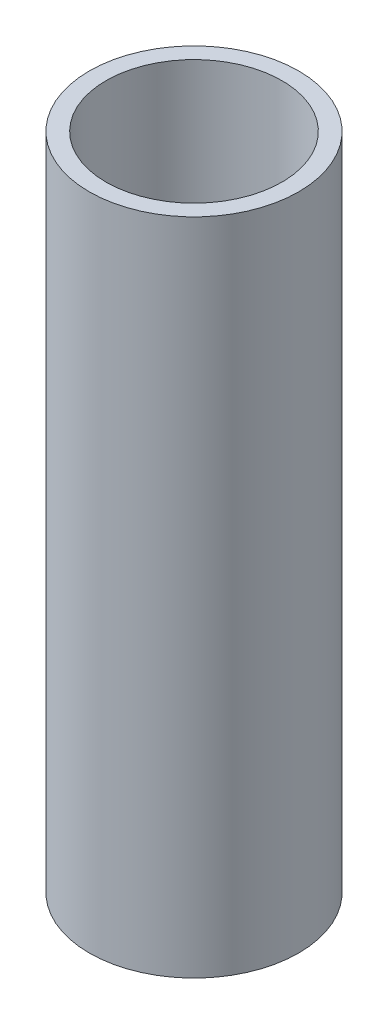
SolidWorks part; units mm, degrees
ref_plane "前视基准面" through (0, 0, 0) normal (0, 0, 1) x (1, 0, 0)
ref_plane "上视基准面" through (0, 0, 0) normal (0, 1, 0) x (1, 0, 0)
ref_plane "右视基准面" through (0, 0, 0) normal (1, 0, 0) x (0, 0, -1)
sketch "草图1" plane through (0, 0, 0) normal (0, 1, 0) x (1, 0, 0)
  circle A0 centre (0, 0) radius 2.667
  circle A1 centre (0, 0) radius 3.175
  dimension "D1" = 5.334
  dimension "D2" = 6.35
extrude "凸台-拉伸1" add sketch "草图1" along normal blind 19.9898
